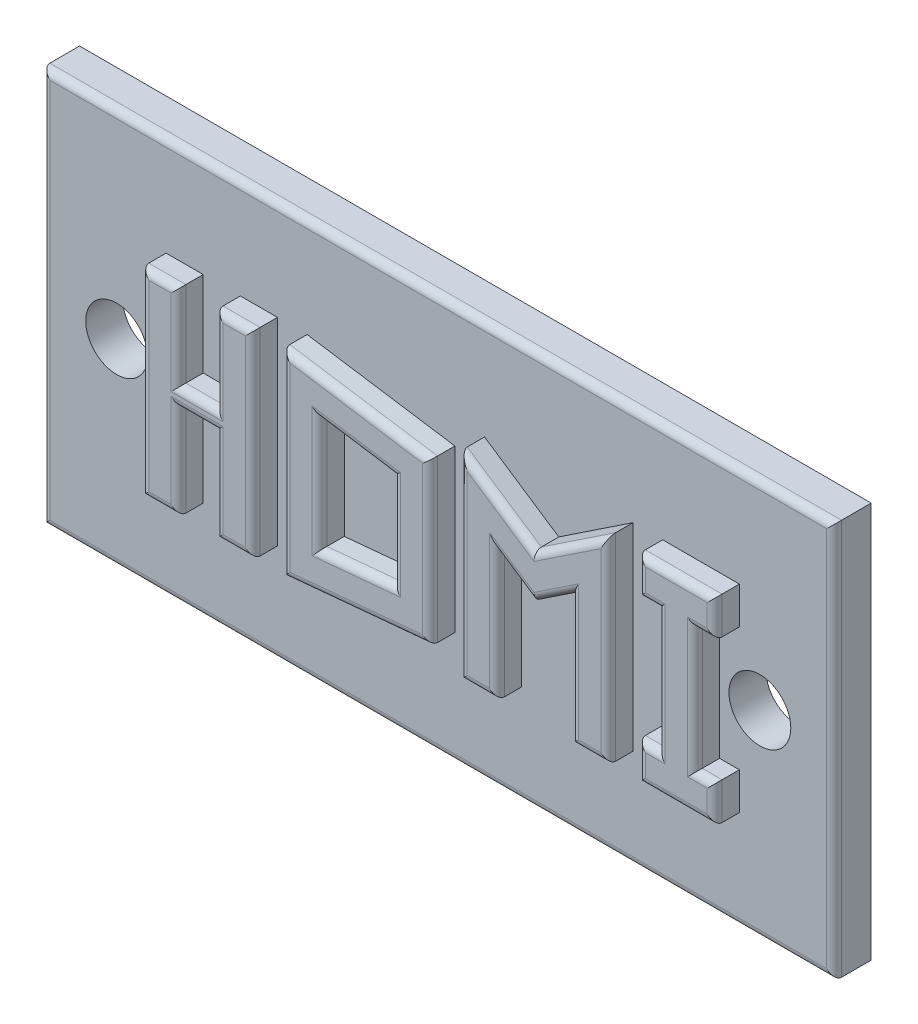
SolidWorks part; units mm, degrees
ref_plane "Спереди" through (0, 0, 0) normal (0, 0, 1) x (1, 0, 0)
ref_plane "Сверху" through (0, 0, 0) normal (0, 1, 0) x (1, 0, 0)
ref_plane "Справа" through (0, 0, 0) normal (1, 0, 0) x (0, 0, -1)
sketch "Эскиз1" plane through (0, 0, 0) normal (0, 0, 1) x (1, 0, 0)
  line L1 (-16, 8) -> (16, 8)
  line L2 (-16, 8) -> (-16, -8)
  line L3 (-16, -8) -> (16, -8)
  line L4 (16, 8) -> (16, -8)
  circle A0 centre (-13, 0) radius 1.25
  circle A1 centre (13, 0) radius 1.25
  dimension "D7" = 2.5
  dimension "D8" = 2.5
  dimension "D1" = 32
  dimension "D2" = 16
  dimension "D3" = 16
  dimension "D4" = 8
  dimension "D5" = 3
  dimension "D6" = 3
extrude "Бобышка-Вытянуть1" add sketch "Эскиз1" along normal blind 1.5
sketch "Эскиз3" plane through (0, 0, 1.5) normal (0, 0, 1) x (1, 0, 0)
  line L0 (-11, 4) -> (-11, -4)
  line L1 (-11, -4) -> (-9.5, -4)
  line L2 (-9.5, -4) -> (-9.5, -0.2171)
  line L3 (-9.5, -0.2171) -> (-8, -0.2171)
  line L4 (-8, -0.2171) -> (-8, -4)
  line L5 (-8, -4) -> (-6.5, -4)
  line L6 (-6.5, -4) -> (-6.5, 4)
  line L7 (-6.5, 4) -> (-8, 4)
  line L8 (-8, 4) -> (-8, 0.5519)
  line L9 (-8, 0.5519) -> (-9.5, 0.5519)
  line L10 (-9.5, 0.5519) -> (-9.5, 4)
  line L11 (-9.5, 4) -> (-11, 4)
  line L12 (-5.3, 4) -> (-5.3, -4)
  line L13 (-5.3, -4) -> (0.6703, -3.4462)
  line L14 (0.6703, -3.4462) -> (0.6703, 3.084)
  line L15 (0.6703, 3.084) -> (-5.3, 4)
  line L16 (-3.8, 2.2523) -> (-3.8, -2.3171)
  line L17 (-3.8, -2.3171) -> (-0.8297, -2.0416)
  line L18 (-0.8297, -2.0416) -> (-0.8297, 1.7966)
  line L19 (-0.8297, 1.7966) -> (-3.8, 2.2523)
  line L20 (1.8703, 4) -> (1.8703, -4)
  line L21 (1.8703, 4) -> (4.8703, 2)
  line L22 (4.8703, 2) -> (7.8703, 4)
  line L23 (7.8703, 4) -> (7.8703, -4)
  line L24 (7.8703, -4) -> (6.3703, -4)
  line L25 (6.3703, -4) -> (6.3703, 1.1972)
  line L26 (6.3703, 1.1972) -> (4.8703, 0.1972)
  line L27 (4.8703, 0.1972) -> (3.3703, 1.1972)
  line L28 (3.3703, 1.1972) -> (3.3703, -4)
  line L29 (3.3703, -4) -> (1.8703, -4)
  line L30 (16, 8) -> (-16, 8) construction
  line L31 (-16, -8) -> (16, -8) construction
  line L32 (9.0703, 4) -> (12.1703, 4)
  line L33 (12.1703, 4) -> (12.1703, 2.5)
  line L34 (12.1703, 2.5) -> (11.3703, 2.5)
  line L35 (11.3703, 2.5) -> (11.3703, -2.5)
  line L36 (11.3703, -2.5) -> (12.1703, -2.5)
  line L37 (12.1703, -2.5) -> (12.1703, -4)
  line L38 (12.1703, -4) -> (9.0703, -4)
  line L39 (9.0703, -4) -> (9.0703, -2.5)
  line L40 (9.0703, -2.5) -> (9.8703, -2.5)
  line L41 (9.8703, -2.5) -> (9.8703, 2.5)
  line L42 (9.8703, 2.5) -> (9.0703, 2.5)
  line L43 (9.0703, 2.5) -> (9.0703, 4)
  line L44 (-16, 8) -> (-16, -8) construction
  dimension "D1" = 1.5
  dimension "D2" = 1.5
  dimension "D3" = 1.5
  dimension "D4" = 1.5
  dimension "D5" = 1.5
  dimension "D6" = 1.5
  dimension "D7" = 8
  dimension "D8" = 4
  dimension "D9" = 4
  dimension "D10" = 1.5
  dimension "D11" = 1.5371
  dimension "D12" = 1.5
  dimension "D13" = 1.5
  dimension "D14" = 1.5
  dimension "D15" = 8
  dimension "D16" = 8
  dimension "D17" = 1.2
  dimension "D18" = 1.2
  dimension "D19" = 4
  dimension "D20" = 8
  dimension "D21" = 1.5
  dimension "D22" = 1.5
  dimension "D23" = 8
  dimension "D24" = 3
  dimension "D25" = 1.5
  dimension "D26" = 1.5
  dimension "D27" = 6
  dimension "D28" = 4
  dimension "D29" = 1.5
  dimension "D30" = 1.5
  dimension "D31" = 1.5
  dimension "D32" = 1.5
  dimension "D33" = 1.5
  dimension "D34" = 8
  dimension "D35" = 4
  dimension "D36" = 0.8
  dimension "D37" = 0.8
  dimension "D38" = 0.8
  dimension "D39" = 0.8
  dimension "D40" = 1.2
  dimension "D41" = 5
extrude "Бобышка-Вытянуть2" add sketch "Эскиз3" along normal blind 1
fillet "Скругление2" radius 0.3 46 edges at (10.6203, 4, 2.5) (12.1703, 3.25, 2.5) (11.7703, 2.5, 2.5) (11.3703, 0, 2.5) (11.7703, -2.5, 2.5) (12.1703, -3.25, 2.5) (10.6203, -4, 2.5) (9.0703, -3.25, 2.5) (9.4703, -2.5, 2.5) (9.8703, 0, 2.5) (9.4703, 2.5, 2.5) (9.0703, 3.25, 2.5) (1.8703, 0, 2.5) (3.3703, 3, 2.5) (6.3703, 3, 2.5) (7.8703, 0, 2.5) (7.1203, -4, 2.5) (6.3703, -1.4014, 2.5) (5.6203, 0.6972, 2.5) (4.1203, 0.6972, 2.5) (3.3703, -1.4014, 2.5) (2.6203, -4, 2.5) (-2.3149, -2.1794, 2.5) (-0.8297, -0.1225, 2.5) (-2.3149, 2.0245, 2.5) (-3.8, -0.0324, 2.5) (0.6703, -0.1811, 2.5) (-2.3149, -3.7231, 2.5) (-5.3, 0, 2.5) (-2.3149, 3.542, 2.5) (-9.5, 2.2759, 2.5) (-8.75, 0.5519, 2.5) (-8, 2.2759, 2.5) (-7.25, 4, 2.5) (-6.5, 0, 2.5) (-7.25, -4, 2.5) (-8, -2.1086, 2.5) (-8.75, -0.2171, 2.5) (-9.5, -2.1086, 2.5) (-10.25, -4, 2.5) (-11, 0, 2.5) (-10.25, 4, 2.5) (-16, 0, 1.5) (0, -8, 1.5) (16, 0, 1.5) (0, 8, 1.5)
